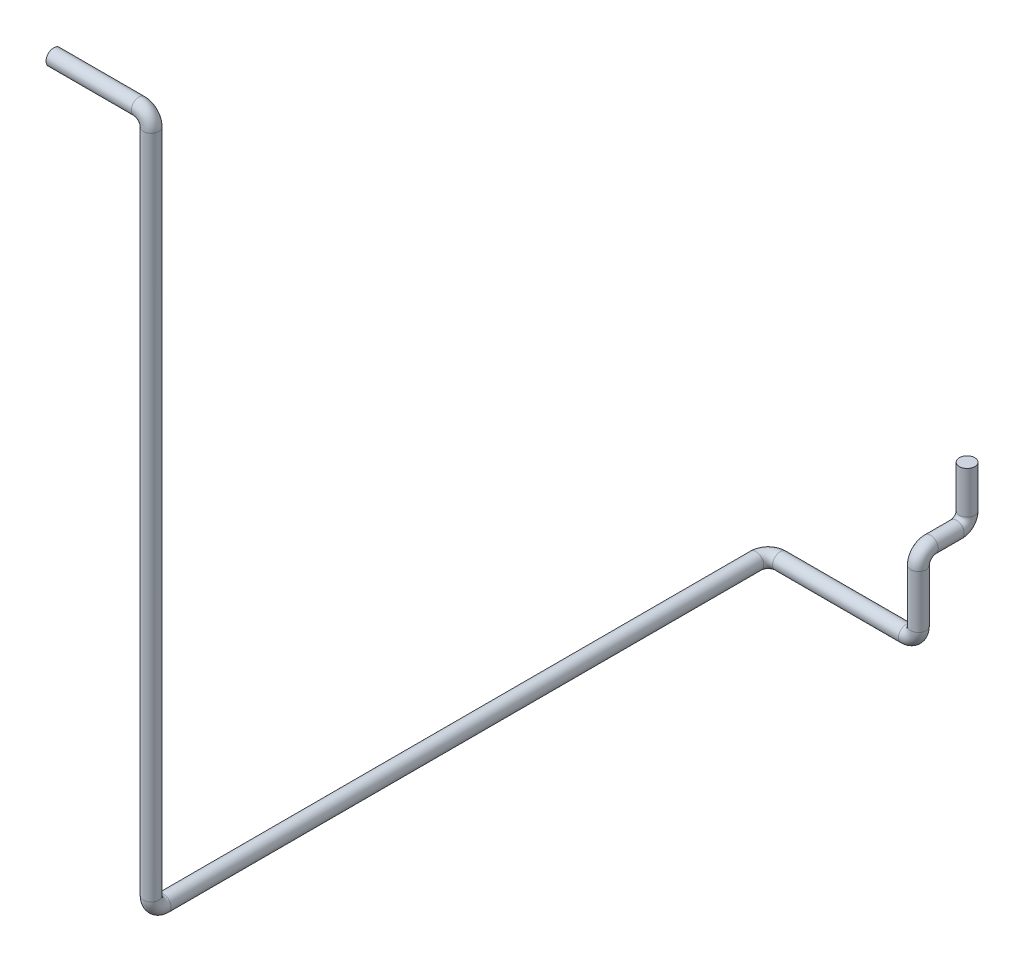
SolidWorks part; units mm, degrees
ref_plane "Alzado" through (0, 0, 0) normal (0, 0, 1) x (1, 0, 0)
ref_plane "Planta" through (0, 0, 0) normal (0, 1, 0) x (1, 0, 0)
ref_plane "Vista lateral" through (0, 0, 0) normal (1, 0, 0) x (0, 0, -1)
sketch "Croquis1" plane through (0, 0, 0) normal (0, 1, 0) x (1, 0, 0)
  circle A0 centre (0, 0) radius 9.525
  dimension "D1" = 19.05
extrude "Saliente-Extruir1" add sketch "Croquis1" against normal blind 10
sketch3d "Croquis3D1"
  line L0 (0, -10, 0) -> (0, -52, 0)
  line L1 (0, -10, 0) -> (0, 0, 0) construction
  line L2 (0, -65, 13) -> (0, -65, 45)
  line L3 (0, -80, 60) -> (0, -145, 60)
  line L4 (-15, -160, 60) -> (-170, -160, 60)
  line L5 (-185, -160, 75) -> (-185, -160, 805)
  line L6 (-185, -145, 820) -> (-185, 675, 820)
  line L7 (-200, 690, 820) -> (-305, 690, 820)
  arc A0 (0, -65, 45) -> (0, -80, 60) centre (0, -80, 45) ccw
  arc A1 (-185, -160, 805) -> (-185, -145, 820) centre (-185, -145, 805) ccw
  arc A2 (-170, -160, 60) -> (-185, -160, 75) centre (-170, -160, 75) ccw
  arc A3 (0, -52, 0) -> (0, -65, 13) centre (0, -52, 13) ccw
  arc A4 (0, -145, 60) -> (-15, -160, 60) centre (-15, -145, 60) ccw
  arc A5 (-185, 675, 820) -> (-200, 690, 820) centre (-200, 675, 820) ccw
  point P10 (50, 265, 735)
  point P12 (0, -65, 60)
  point P14 (50, -65, 735)
  point P15 (15, -80, 45)
  point P18 (0, -65, 735)
  point P19 (-185, -160, 820)
  point P22 (0, -65, 0)
  point P23 (-13, -52, 13)
  point P24 (-200, -145, 805)
  point P27 (-185, -160, 60)
  point P28 (-170, -145, 75)
  point P31 (0, -160, 60)
  point P32 (-15, -145, 45)
  point P35 (-185, 690, 820)
  point P36 (-200, 675, 835)
  dimension "D6" = 95
  dimension "D7" = 13
  dimension "D12" = 15
  dimension "D13" = 15
  dimension "D14" = 15
  dimension "D1" = 55
  dimension "D2" = 735
  dimension "D3" = 50
  dimension "D5" = 60
  dimension "D4" = 330
  dimension "D8" = 185
  dimension "D9" = 760
  dimension "D10" = 850
  dimension "D11" = 120
sketch "Croquis2" plane through (0, -10, 0) normal (0, -1, 0) x (1, 0, 0)
  circle A0 centre (0, 0) radius 9.525
sweep "Barrer1" add profiles "Croquis2" path "Croquis3D1"
